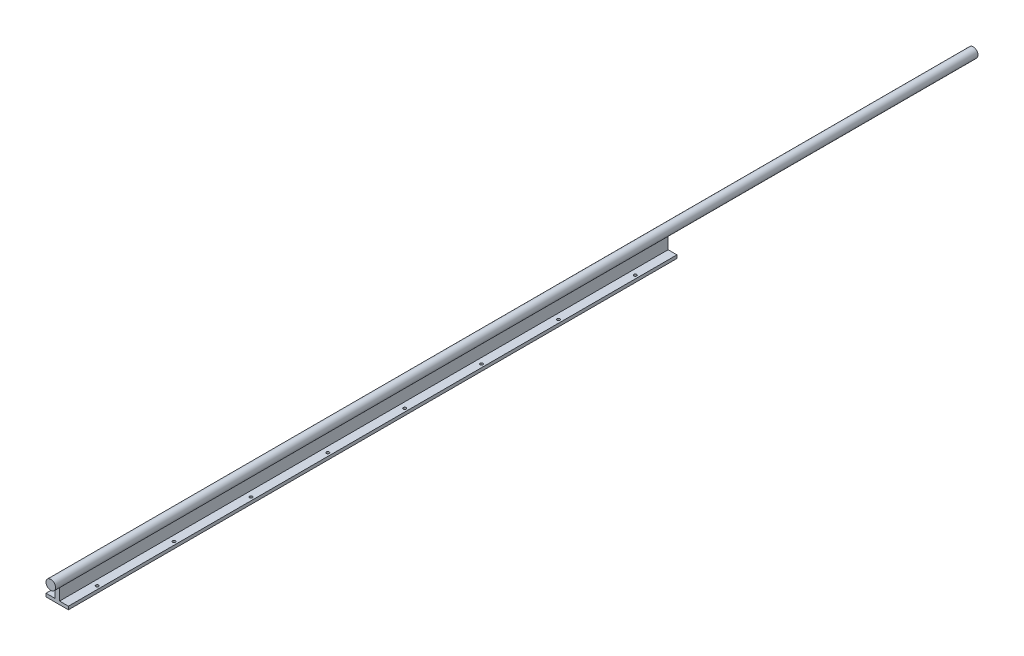
SolidWorks part; units mm, degrees
ref_plane "Front" through (0, 0, 0) normal (0, 0, 1) x (1, 0, 0)
ref_plane "Top" through (0, 0, 0) normal (0, 1, 0) x (1, 0, 0)
ref_plane "Right" through (0, 0, 0) normal (1, 0, 0) x (0, 0, -1)
sketch "Sketch1" plane through (0, 0, 0) normal (0, 0, 1) x (1, 0, 0)
  line L0 (-22.225, -38.1) -> (22.225, -38.1)
  line L1 (22.225, -38.1) -> (22.225, -31.75)
  line L2 (22.225, -31.75) -> (4.7625, -31.75)
  line L3 (4.7625, -31.75) -> (4.7625, -8.2489)
  line L4 (-22.225, -38.1) -> (-22.225, -31.75)
  line L5 (-22.225, -31.75) -> (-4.7625, -31.75)
  line L6 (-4.7625, -31.75) -> (-4.7625, -8.2489)
  arc A0 (4.7625, -8.2489) -> (-4.7625, -8.2489) centre (0, 0) ccw
  dimension "D1" = 19.05
  dimension "D2" = 38.1
  dimension "D3" = 44.45
  dimension "D4" = 9.525
  dimension "D5" = 6.35
extrude "Extrude1" add sketch "Sketch1" along normal blind 1219.2
hole_wizard "#10 Clearance Hole1" positions "Sketch3" profile "Sketch2" hole size "#10" standard "Ansi Inch" end condition up to next
sketch "Sketch3" plane through (0, -38.1, 0) normal (0, -1, 0) x (1, 0, 0)
  line L0 (-22.225, 0) -> (22.225, 0) construction
  point P1 (-15.875, 76.2)
  point P3 (15.875, 76.2)
  dimension "D1" = 15.875
  dimension "D2" = 31.75
  dimension "D3" = 76.2
sketch "Sketch2" plane through (-15.875, -38.1, 76.2) normal (1, 0, 0) x (0, 0, -1)
  line L0 (0, 0) -> (0, 6.35)
  line L1 (0, 6.35) -> (2.8067, 6.35)
  line L2 (2.8067, 6.35) -> (2.8067, 0)
  line L5 (2.8067, 0) -> (0, 0)
  line L11 (0, -6.35) -> (0, 107.95) construction
  dimension "Thru Hole Dia." = 5.6134
  dimension "Thru Hole Depth" = 6.35
pattern_linear "LPattern3" count 8 spacing 152.4 along (0, 0, 1) of "#10 Clearance Hole1"
sketch "Sketch4" plane through (0, 0, 1219.2) normal (0, 0, 1) x (1, 0, 0)
  circle A0 centre (0, 0) radius 9.525
  arc A1 (4.7625, -8.2489) -> (-4.7625, -8.2489) centre (0, 0) ccw construction
extrude "Cut-Extrude1" cut sketch "Sketch4" against normal blind 12.7 flip side to cut
sketch "Sketch5" plane through (0, 0, 0) normal (0, 0, -1) x (-1, 0, 0)
  circle A0 centre (0, 0) radius 9.525
  arc A1 (4.7625, -8.2489) -> (-4.7625, -8.2489) centre (0, 0) ccw construction
extrude "Extrude2" add sketch "Sketch5" along normal blind 609.6
